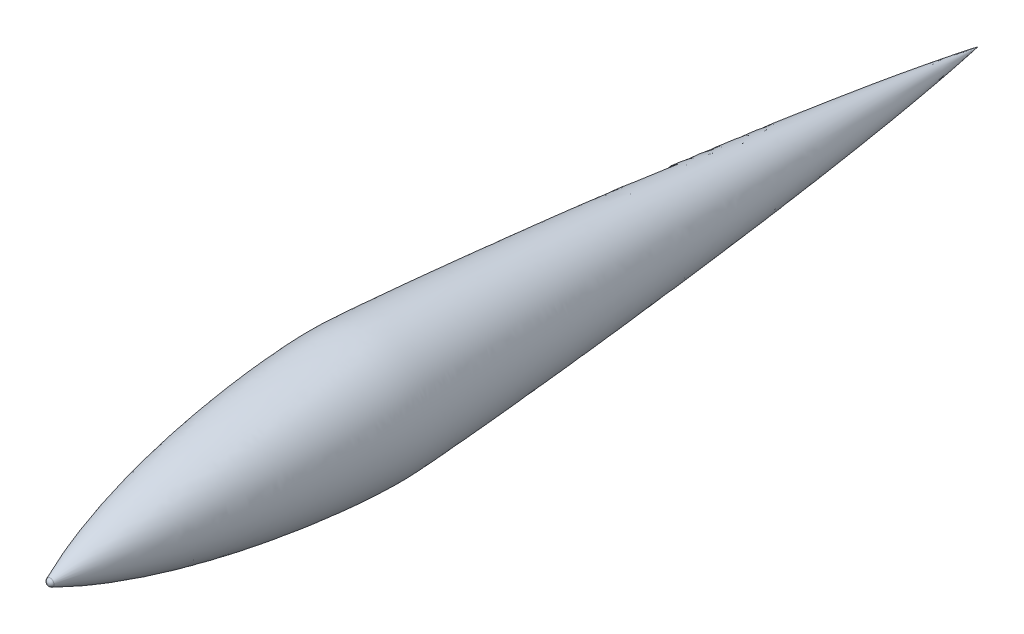
SolidWorks part; units mm, degrees
ref_plane "Front Plane" through (0, 0, 0) normal (0, 0, 1) x (1, 0, 0)
ref_plane "Top Plane" through (0, 0, 0) normal (0, 1, 0) x (1, 0, 0)
ref_plane "Right Plane" through (0, 0, 0) normal (1, 0, 0) x (0, 0, -1)
sketch "Sketch1" plane through (0, 0, 0) normal (1, 0, 0) x (0, 0, -1)
  line L0 (0, 0) -> (331.9915, 0) construction
  line L1 (0, 0) -> (0, 15) construction
  line L2 (19.7927, 15) -> (-9.9589, 15) construction
  line L3 (-75, 0) -> (150, 0)
  line L4 (148.0582, 104.0138) -> (-297.0839, -103.5594) construction
  line L5 (819.866, -118.1155) -> (-518.9679, 117.9571) construction
  line L6 (-73.5723, 0) -> (-73.5723, 0.6512) construction
  arc A0 (-72.9737, 0.9159) -> (-73.5723, 0) centre (-72.5723, 0) ccw
  spline S0 degree 3 poles (-75, 0) (-51.8892, 10.7768) (-8.7109, 15.4353) (20.0191, 14.3467) (111.5925, 6.7723) (150, 0) knots 0 0 0 0 0.313878 0.413878 1 1 1 1
  dimension "D2" = 75
  dimension "D4" = 155
  dimension "D5" = 170
  dimension "D6" = 130
  dimension "D7" = 85
  dimension "D8" = 115
  dimension "D9" = 1
  dimension "D1" = 15
  dimension "D3" = 150
revolve "Revolve1" add sketch "Sketch1" angle 360 about L0
